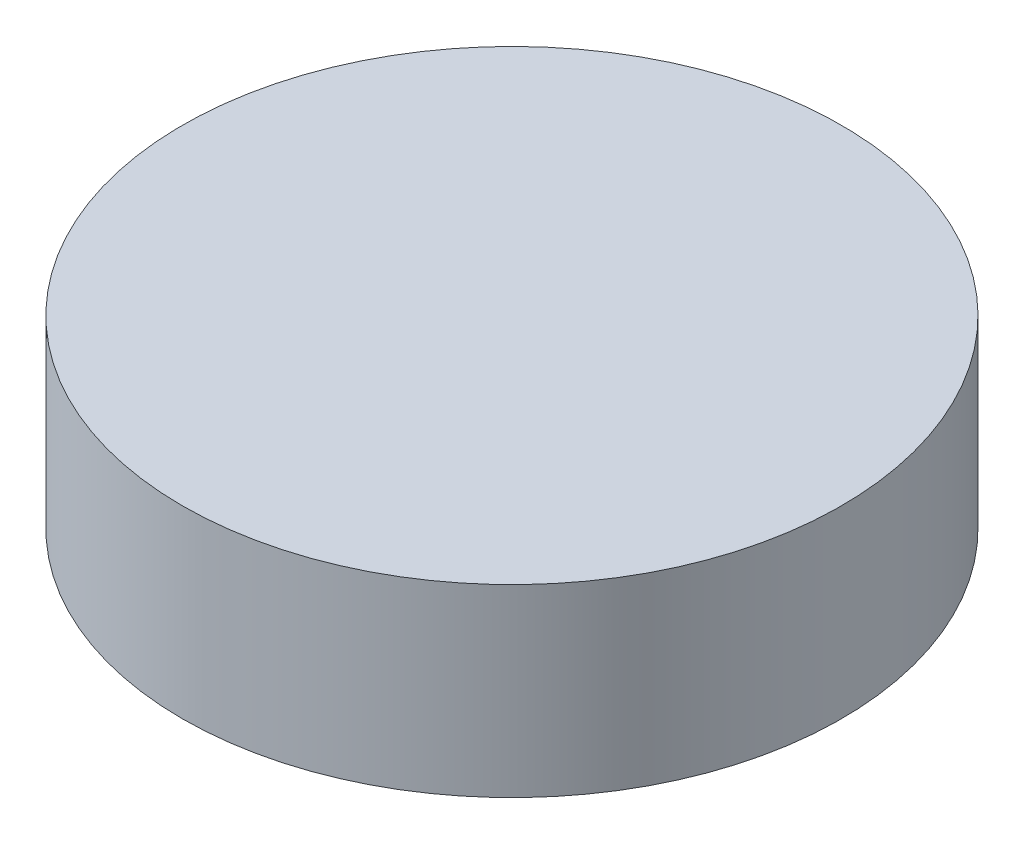
SolidWorks part; units mm, degrees
ref_plane "Front Plane" through (0, 0, 0) normal (0, 0, 1) x (1, 0, 0)
ref_plane "Top Plane" through (0, 0, 0) normal (0, 1, 0) x (1, 0, 0)
ref_plane "Right Plane" through (0, 0, 0) normal (1, 0, 0) x (0, 0, -1)
sketch "Sketch1" plane through (0, 0, 0) normal (0, 1, 0) x (1, 0, 0)
  circle A0 centre (0, 0) radius 1.59
  dimension "D1" = 3.18
extrude "Boss-Extrude1" add sketch "Sketch1" along normal blind 0.89
